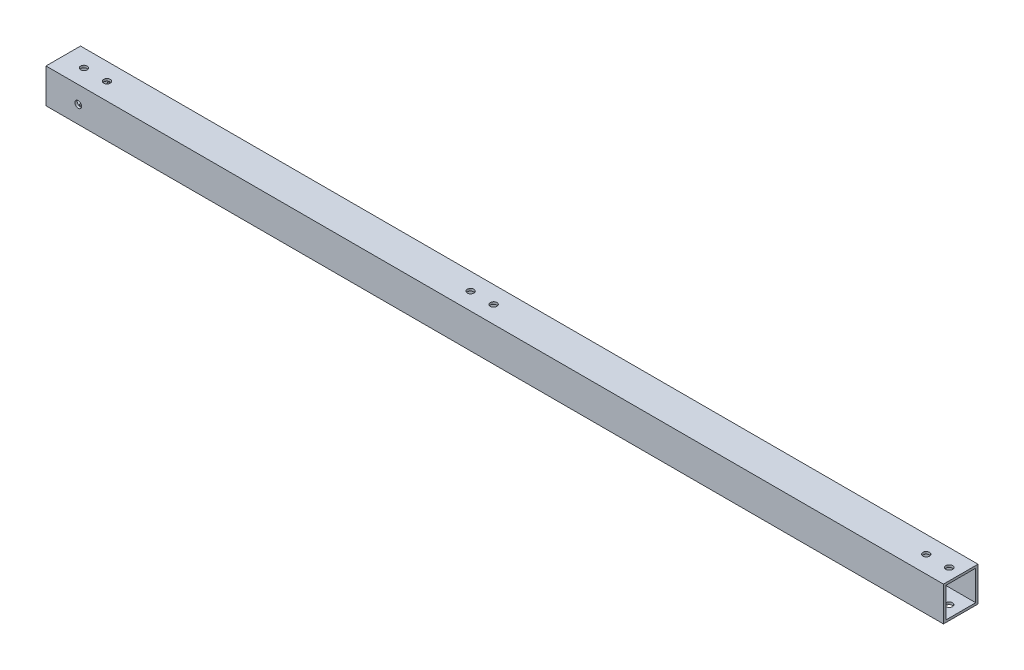
SolidWorks part; units mm, degrees
material "Thornel Mat VMA"
ref_plane "前视基准面" through (0, 0, 0) normal (0, 0, 1) x (1, 0, 0)
ref_plane "上视基准面" through (0, 0, 0) normal (0, 1, 0) x (1, 0, 0)
ref_plane "右视基准面" through (0, 0, 0) normal (1, 0, 0) x (0, 0, -1)
other "Configuration Table"
sketch "草图1" plane through (0, 0, 0) normal (1, 0, 0) x (0, 0, -1)
  line L0 (-6.5, -6.5) -> (-6.5, 6.5)
  line L1 (-7.5, -7.5) -> (7.5, -7.5)
  line L2 (-7.5, -7.5) -> (-7.5, 7.5)
  line L3 (-7.5, 7.5) -> (7.5, 7.5)
  line L4 (7.5, -7.5) -> (7.5, 7.5)
  line L5 (-7.5, -7.5) -> (7.5, 7.5) construction
  line L6 (-7.5, 7.5) -> (7.5, -7.5) construction
  line L7 (-6.5, 6.5) -> (6.5, 6.5)
  line L8 (6.5, -6.5) -> (6.5, 6.5)
  line L9 (-6.5, -6.5) -> (6.5, -6.5)
  point P0 (0, 0)
  dimension "D1" = 15
  dimension "D2" = 15
  dimension "D3" = 1
extrude "凸台-拉伸1" add sketch "草图1" along normal blind 390
sketch "草图2" plane through (0, -7.5, 0) normal (0, -1, 0) x (1, 0, 0)
  line L0 (0, 0) -> (434.0441, 0) construction
  circle A0 centre (375, 0) radius 1.45 construction
  circle A1 centre (385, 0) radius 1.45 construction
  circle A2 centre (9, 0) radius 1.45 construction
  circle A3 centre (19, 0) radius 1.45 construction
  circle A4 centre (375, 0) radius 1.45
  circle A5 centre (385, 0) radius 1.45
  circle A6 centre (9, 0) radius 1.45
  circle A7 centre (19, 0) radius 1.45
  circle A8 centre (177, 0) radius 1.45
  circle A9 centre (187, 0) radius 1.45
  dimension "D1" = 2.9
  dimension "D3" = 2.9
  dimension "D4" = 187
  dimension "D2" = 177
extrude "切除-拉伸1" cut sketch "草图2" against normal through all
sketch "草图3" plane through (0, 0, -7.5) normal (0, 0, -1) x (-1, 0, 0)
  circle A0 centre (-14, 0) radius 1.45 construction
  circle A1 centre (-14, 0) radius 1.45
extrude "切除-拉伸2" cut sketch "草图3" against normal through all
